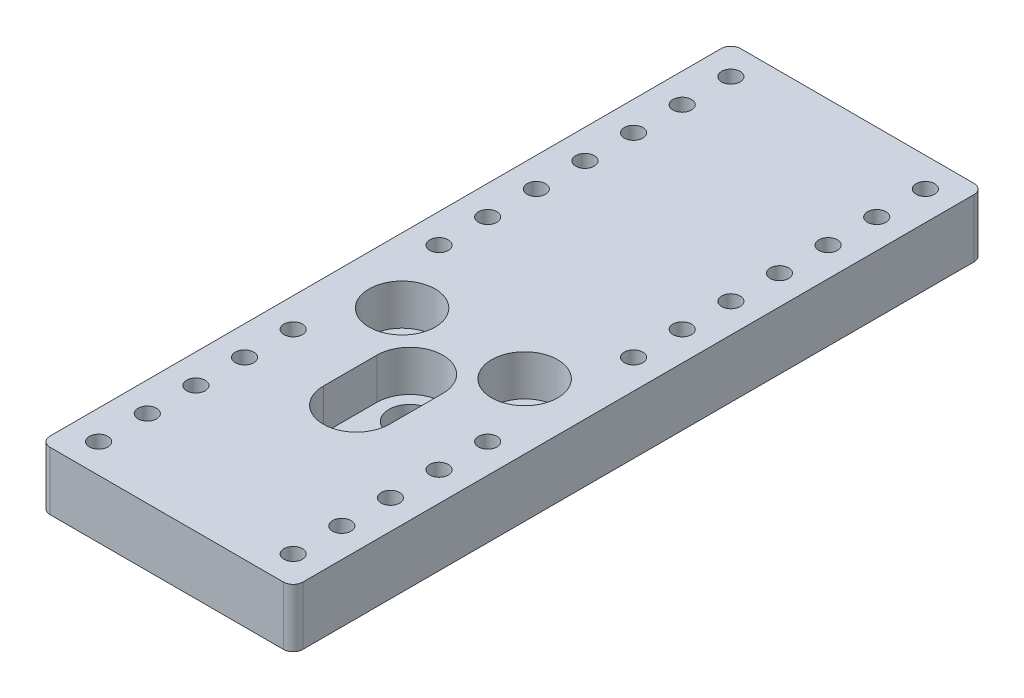
SolidWorks part; units mm, degrees
ref_plane "Front Plane" through (0, 0, 0) normal (0, 0, 1) x (1, 0, 0)
ref_plane "Top Plane" through (0, 0, 0) normal (0, 1, 0) x (1, 0, 0)
ref_plane "Right Plane" through (0, 0, 0) normal (1, 0, 0) x (0, 0, -1)
sketch "Sketch1" plane through (0, 0, 0) normal (0, 1, 0) x (1, 0, 0)
  line L1 (-13, -35.5) -> (13, -35.5)
  line L2 (-13, -35.5) -> (-13, 35.5)
  line L3 (-13, 35.5) -> (13, 35.5)
  line L4 (13, -35.5) -> (13, 35.5)
  line L5 (-13, -35.5) -> (13, 35.5) construction
  line L6 (-13, 35.5) -> (13, -35.5) construction
  point P0 (0, 0)
  dimension "D4" = 26
  dimension "D6" = 71
extrude "Boss-Extrude1" add sketch "Sketch1" along normal blind 6
sketch "Sketch10" plane through (0, 6, 0) normal (0, 1, 0) x (1, 0, 0)
  line L0 (0, -10.5) -> (0, -35.5) construction
  line L1 (-13, -35.5) -> (13, -35.5) construction
  circle A0 centre (0, -10.5) radius 2.15
  circle A1 centre (0, -16) radius 2.15
  circle A2 centre (-6.3, -5) radius 2.15
  circle A3 centre (6.3, -5) radius 2.15
  dimension "D1" = 4.3
  dimension "D2" = 5.5
  dimension "D3" = 5.5
  dimension "D4" = 6.3
  dimension "D5" = 25
extrude "Cut-Extrude9" cut sketch "Sketch10" against normal up to next
sketch "Sketch11" plane through (0, 6, 0) normal (0, 1, 0) x (1, 0, 0)
  line L0 (0, -10.5) -> (0, -16) construction
  line L1 (3.4, -10.5) -> (3.4, -16)
  line L2 (-3.4, -10.5) -> (-3.4, -16)
  circle A0 centre (-6.3, -5) radius 3.4
  circle A1 centre (6.3, -5) radius 3.4
  arc A2 (3.4, -10.5) -> (-3.4, -10.5) centre (0, -10.5) ccw
  arc A3 (-3.4, -16) -> (3.4, -16) centre (0, -16) ccw
  point P9 (0, -13.25)
  dimension "D1" = 6.8
  dimension "D2" = 6.8
extrude "Cut-Extrude10" cut sketch "Sketch11" against normal blind 4.2
sketch "Sketch5" plane through (0, 6, 0) normal (0, 1, 0) x (1, 0, 0)
  line L0 (0, 0) -> (0, -35.5) construction
  line L1 (-13, -35.5) -> (13, -35.5) construction
  line L2 (13, 35.5) -> (-13, 35.5) construction
  circle A0 centre (-10, 32.5) radius 0.95
  circle A1 centre (10, 32.5) radius 0.95
  dimension "D3" = 1.9
  dimension "D1" = 20
  dimension "D2" = 3
extrude "Cut-Extrude4" cut sketch "Sketch5" against normal offset from surface (5 mm away) 1 up to face at (0, 0, 13.85)
pattern_linear "LPattern1" count 7 spacing 5 along (0, 0, 1) of "Cut-Extrude4"
mirror "Mirror2" about plane through (0, 0, 0) normal (0, 0, 1) of "Cut-Extrude4"
pattern_linear "LPattern2" count 5 spacing 5 along (0, 0, -1) of "Mirror2"
fillet "Fillet1" radius 1 4 edges at (-13, 3, -35.5) (-13, 3, 35.5) (13, 3, 35.5) (13, 3, -35.5)
